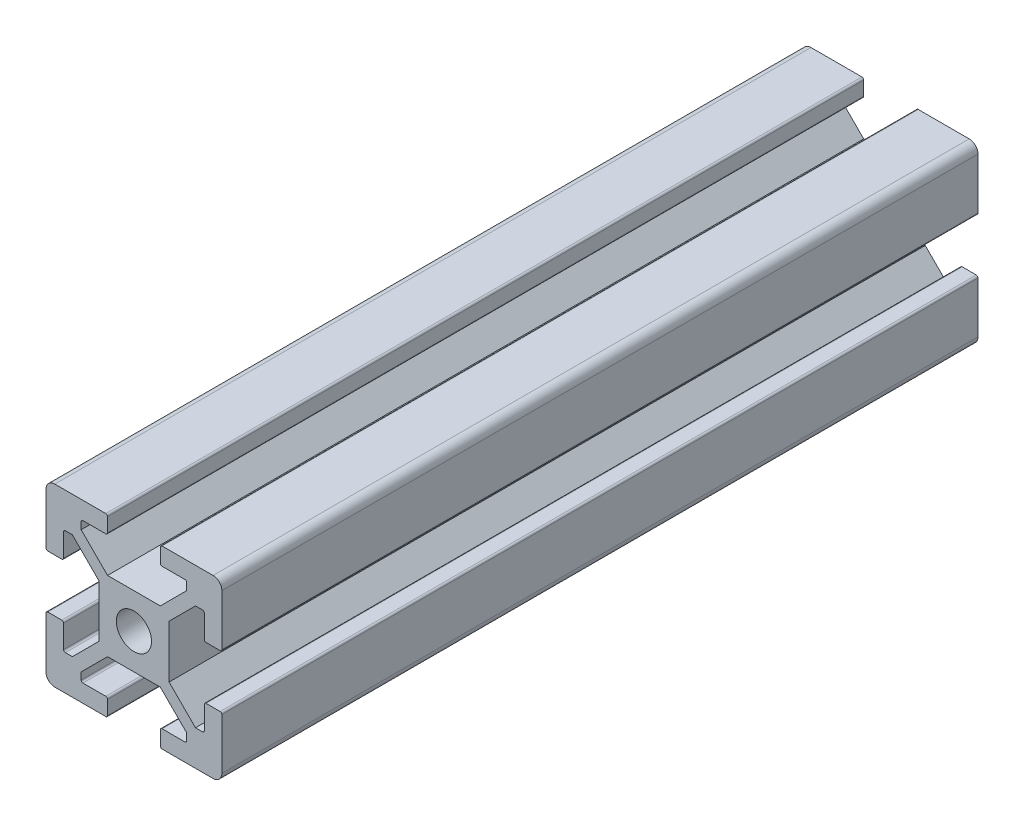
SolidWorks part; units mm, degrees
material "1060 Alloy"
ref_plane "Front Plane" through (0, 0, 0) normal (0, 0, 1) x (1, 0, 0)
ref_plane "Top Plane" through (0, 0, 0) normal (0, 1, 0) x (1, 0, 0)
ref_plane "Right Plane" through (0, 0, 0) normal (1, 0, 0) x (0, 0, -1)
sketch "Sketch1" plane through (0, 0, 0) normal (0, 0, 1) x (1, 0, 0)
  circle A28 centre (0, 0) radius 2
  point P0 (0, 0)
  line B0 (-3.2, 8) -> (-5.8005, 8)
  line B1 (-6.0005, 7.8005) -> (-6.0027, 7.0027)
  line B2 (-6.0027, 7.0027) -> (-3, 4)
  line B3 (-3, 4) -> (3, 4)
  line B4 (3, 4) -> (6.0027, 7.0027)
  line B5 (6.0027, 7.0027) -> (6.0005, 7.8005)
  line B6 (5.8005, 8) -> (3.2, 8)
  line B7 (3, 8.2) -> (3, 9.8)
  line B8 (3.2, 10) -> (9, 10)
  line B9 (10, 9) -> (10, 3.2)
  line B10 (9.8, 3) -> (8.2, 3)
  line B11 (8, 3.2) -> (8, 5.8005)
  line B12 (7.8005, 6.0005) -> (7.0027, 6.0027)
  line B13 (7.0027, 6.0027) -> (4, 3)
  line B14 (4, 3) -> (4, -3)
  line B15 (4, -3) -> (7.0027, -6.0027)
  line B16 (7.0027, -6.0027) -> (7.8005, -6.0005)
  line B17 (8, -5.8005) -> (8, -3.2)
  line B18 (8.2, -3) -> (9.8, -3)
  line B19 (10, -3.2) -> (10, -9)
  line B20 (9, -10) -> (3.2, -10)
  line B21 (3, -9.8) -> (3, -8.2)
  line B22 (3.2, -8) -> (5.8005, -8)
  line B23 (6.0005, -7.8005) -> (6.0027, -7.0027)
  line B24 (6.0027, -7.0027) -> (3, -4)
  line B25 (3, -4) -> (-3, -4)
  line B26 (-3, -4) -> (-6.0027, -7.0027)
  line B27 (-6.0027, -7.0027) -> (-6.0005, -7.8005)
  line B28 (-5.8005, -8) -> (-3.2, -8)
  line B29 (-3, -8.2) -> (-3, -9.8)
  line B30 (-3.2, -10) -> (-9, -10)
  line B31 (-10, -9) -> (-10, -3.2)
  line B32 (-9.8, -3) -> (-8.2, -3)
  line B33 (-8, -3.2) -> (-8, -5.8005)
  line B34 (-7.8005, -6.0005) -> (-7.0027, -6.0027)
  line B35 (-7.0027, -6.0027) -> (-4, -3)
  line B36 (-4, -3) -> (-4, 3)
  line B37 (-4, 3) -> (-7.0027, 6.0027)
  line B38 (-7.0027, 6.0027) -> (-7.8005, 6.0005)
  line B39 (-8, 5.8005) -> (-8, 3.2)
  line B40 (-8.2, 3) -> (-9.8, 3)
  line B41 (-10, 3.2) -> (-10, 9)
  line B42 (-9, 10) -> (-3.2, 10)
  line B43 (-3, 9.8) -> (-3, 8.2)
  line B44 (0, -4) -> (0, 4) construction
  line B45 (-4, 0) -> (4, 0) construction
  arc B46 (-5.8005, 8) -> (-6.0005, 7.8005) centre (-5.8005, 7.8) ccw
  arc B47 (6.0005, 7.8005) -> (5.8005, 8) centre (5.8005, 7.8) ccw
  arc B48 (3, 8.2) -> (3.2, 8) centre (3.2, 8.2) ccw
  arc B49 (3.2, 10) -> (3, 9.8) centre (3.2, 9.8) ccw
  arc B50 (10, 9) -> (9, 10) centre (9, 9) ccw
  arc B51 (9.8, 3) -> (10, 3.2) centre (9.8, 3.2) ccw
  arc B52 (8, 3.2) -> (8.2, 3) centre (8.2, 3.2) ccw
  arc B53 (8, 5.8005) -> (7.8005, 6.0005) centre (7.8, 5.8005) ccw
  arc B54 (7.8005, -6.0005) -> (8, -5.8005) centre (7.8, -5.8005) ccw
  arc B55 (8.2, -3) -> (8, -3.2) centre (8.2, -3.2) ccw
  arc B56 (10, -3.2) -> (9.8, -3) centre (9.8, -3.2) ccw
  arc B57 (9, -10) -> (10, -9) centre (9, -9) ccw
  arc B58 (3, -9.8) -> (3.2, -10) centre (3.2, -9.8) ccw
  arc B59 (3.2, -8) -> (3, -8.2) centre (3.2, -8.2) ccw
  arc B60 (5.8005, -8) -> (6.0005, -7.8005) centre (5.8005, -7.8) ccw
  arc B61 (-6.0005, -7.8005) -> (-5.8005, -8) centre (-5.8005, -7.8) ccw
  arc B62 (-3, -8.2) -> (-3.2, -8) centre (-3.2, -8.2) ccw
  arc B63 (-3.2, -10) -> (-3, -9.8) centre (-3.2, -9.8) ccw
  arc B64 (-10, -9) -> (-9, -10) centre (-9, -9) ccw
  arc B65 (-9.8, -3) -> (-10, -3.2) centre (-9.8, -3.2) ccw
  arc B66 (-8, -3.2) -> (-8.2, -3) centre (-8.2, -3.2) ccw
  arc B67 (-8, -5.8005) -> (-7.8005, -6.0005) centre (-7.8, -5.8005) ccw
  arc B68 (-7.8005, 6.0005) -> (-8, 5.8005) centre (-7.8, 5.8005) ccw
  arc B69 (-8.2, 3) -> (-8, 3.2) centre (-8.2, 3.2) ccw
  arc B70 (-10, 3.2) -> (-9.8, 3) centre (-9.8, 3.2) ccw
  arc B71 (-9, 10) -> (-10, 9) centre (-9, 9) ccw
  arc B72 (-3, 9.8) -> (-3.2, 10) centre (-3.2, 9.8) ccw
  arc B73 (-3.2, 8) -> (-3, 8.2) centre (-3.2, 8.2) ccw
  dimension "D1" = 4
sketch_block_instance "Block1-1"
sketch_block "Block1"
extrude "Boss-Extrude1" add sketch "Sketch1" along normal blind 86
